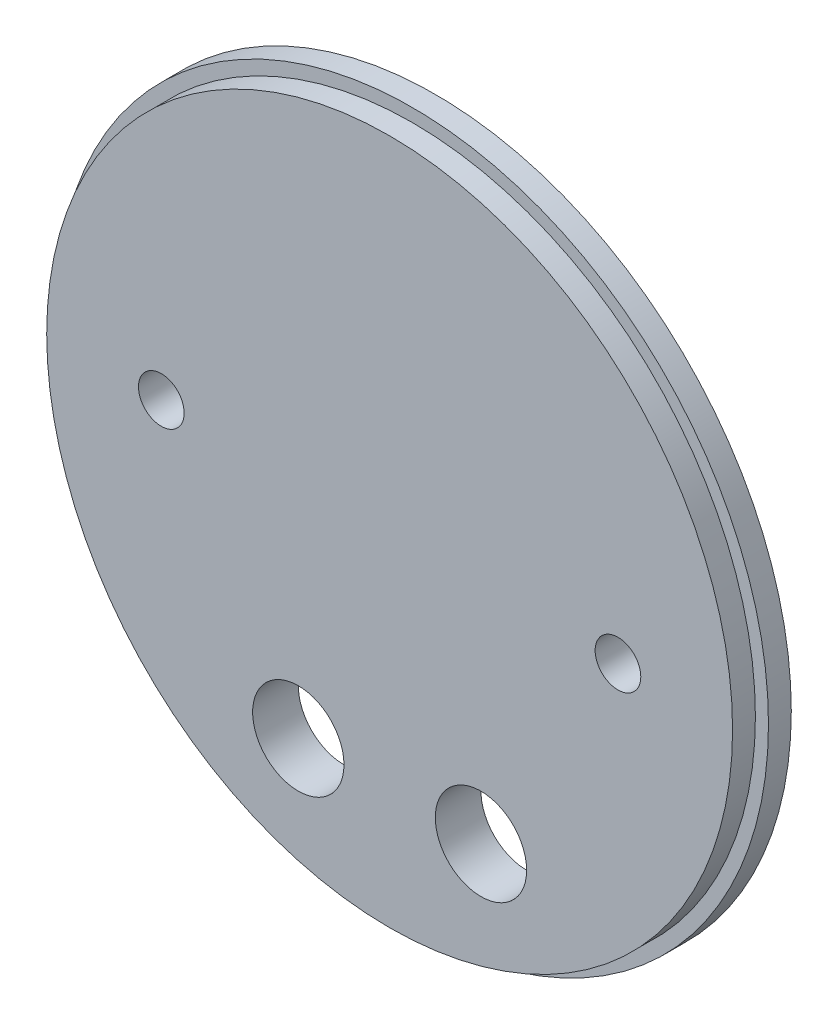
SolidWorks part; units mm, degrees
ref_plane "Front Plane" through (0, 0, 0) normal (0, 0, 1) x (1, 0, 0)
ref_plane "Top Plane" through (0, 0, 0) normal (0, 1, 0) x (1, 0, 0)
ref_plane "Right Plane" through (0, 0, 0) normal (1, 0, 0) x (0, 0, -1)
sketch "Sketch1" plane through (0, 0, 0) normal (0, 0, 1) x (1, 0, 0)
  circle A0 centre (0, 0) radius 49.5046
  dimension "D1" = 99.0092
extrude "Boss-Extrude1" add sketch "Sketch1" along normal blind 3.175
sketch "Sketch2" plane through (0, 0, 3.175) normal (0, 0, 1) x (1, 0, 0)
  circle A0 centre (0, 0) radius 47.6885
  dimension "D1" = 95.377
extrude "Boss-Extrude2" add sketch "Sketch2" along normal blind 3.175
sketch "Sketch3" plane through (0, 0, 6.35) normal (0, 0, 1) x (1, 0, 0)
  circle A0 centre (-12.7, -31.2354) radius 6.35
  circle A1 centre (12.7, -31.2354) radius 6.35
  circle A2 centre (-12.7, -31.2354) radius 12.7 construction
  circle A3 centre (-12.7, -31.2354) radius 13.97 construction
  circle A4 centre (12.7, -31.2354) radius 12.7 construction
  circle A5 centre (12.7, -31.2354) radius 13.97 construction
  circle A6 centre (0, 0) radius 47.6885 construction
  circle A7 centre (0, 0) radius 47.6885 construction
  circle A8 centre (-31.75, 0) radius 3.175
  circle A9 centre (31.75, 0) radius 3.175
  point P16 (0, 0)
  dimension "D1" = 27.94
  dimension "D2" = 25.4
  dimension "D3" = 12.7
  dimension "D4" = 6.35
  dimension "D5" = 6.35
  dimension "D6" = 63.5
  dimension "D7" = 31.75
extrude "Cut-Extrude1" cut sketch "Sketch3" against normal through all
